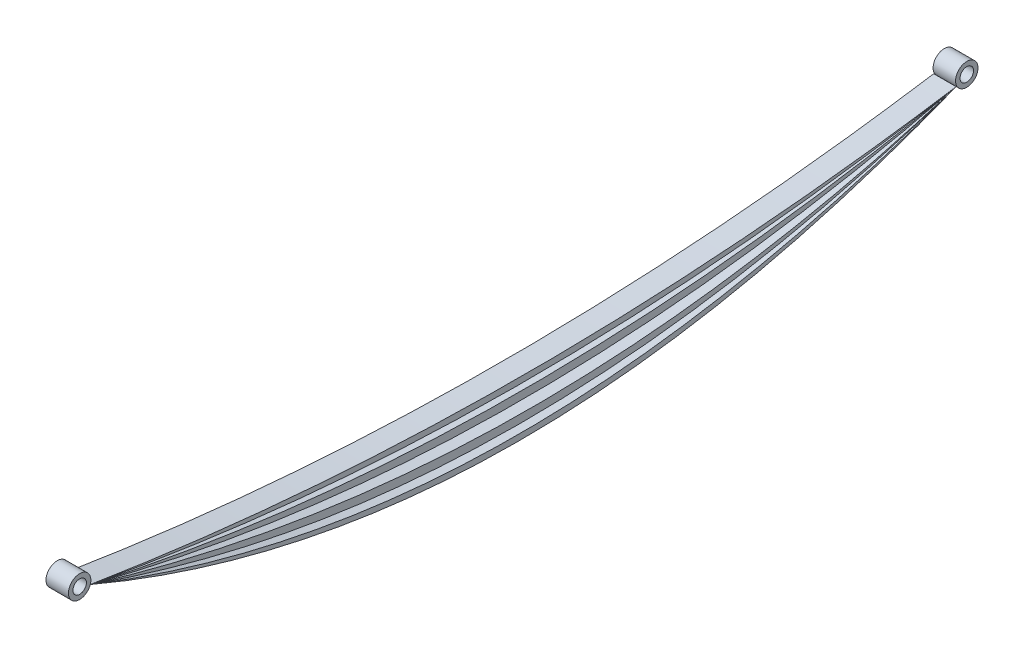
SolidWorks part; units mm, degrees
ref_plane "Front Plane" through (0, 0, 0) normal (0, 0, 1) x (1, 0, 0)
ref_plane "Top Plane" through (0, 0, 0) normal (0, 1, 0) x (1, 0, 0)
ref_plane "Right Plane" through (0, 0, 0) normal (1, 0, 0) x (0, 0, -1)
sketch "Sketch1" plane through (0, 0, 0) normal (1, 0, 0) x (0, 0, -1)
  line L1 (-127.7808, 42.4696) -> (65.0592, 42.08) construction
  line L2 (-31.3608, 56.4803) -> (-31.3608, 9.4168) construction
  circle A0 centre (-130.1522, 43.2614) radius 2.5
  circle A1 centre (67.4305, 43.2614) radius 2.5
  spline S0 degree 2 poles (-127.7808, 42.4696) (-31.7554, 26.9703) (65.0592, 42.08) knots 0 0 0 1 1 1
  spline S1 degree 2 poles (-127.7808, 42.4696) (-32.3332, 17.7907) (65.0592, 42.08) knots 0 0 0 1 1 1
  spline S2 degree 2 poles (-127.7808, 42.4696) (-33.8123, 2.5977) (65.0592, 42.08) knots 0 0 0 1 1 1
  spline S3 degree 2 poles (-127.7808, 42.4696) (-33.1527, 9.0475) (65.0592, 42.08) knots 0 0 0 1 1 1
  spline S4 degree 2 poles (-127.7808, 42.4696) (-32.196, 24.2429) (65.0592, 42.08) knots 0 0 0 1 1 1
  spline S5 degree 2 poles (-127.7808, 42.4696) (-32.7908, 21.3439) (65.0592, 42.08) knots 0 0 0 1 1 1
  spline S6 degree 2 poles (65.0592, 42.08) (-28.6723, 12.5923) (-127.7808, 42.4696) knots 0 0 0 1 1 1
  spline S7 degree 3 poles (65.0592, 42.08) (2.9557, 19.1426) (-60.749, 16.0514) (-127.7808, 42.4696) knots 0 0 0 0 1 1 1 1
  dimension "D2" = 5
  dimension "D1" = 192.84
  dimension "D3" = 197.5826
extrude "Boss-Extrude3" add sketch "Sketch1" along normal blind 5 contours A0 | A1 | S0 S4 | S5 S1 | S3 S6 | S2 S7
sketch "Sketch2" plane through (5, 0, 0) normal (1, 0, 0) x (0, 0, -1)
  circle A0 centre (67.4305, 43.2614) radius 1.5
  circle A1 centre (67.4305, 43.2614) radius 2.5
  circle A2 centre (67.4305, 43.2614) radius 2.5
  dimension "D1" = 0
  dimension "D2" = 1
sketch "Sketch3" plane through (5, 0, 0) normal (1, 0, 0) x (0, 0, -1)
  circle A0 centre (67.4305, 43.2614) radius 1.5
extrude "Cut-Extrude2" cut sketch "Sketch3" against normal blind 5
sketch "Sketch4" plane through (0, 0, 0) normal (-1, 0, 0) x (0, 0, 1)
  circle A0 centre (130.1522, 43.2614) radius 1.5
  circle A1 centre (130.1522, 43.2614) radius 2.5
  circle A2 centre (130.1522, 43.2614) radius 2.5
  circle A3 centre (130.1522, 43.2614) radius 1.5
  dimension "D1" = 0
  dimension "D2" = 1
extrude "Cut-Extrude3" cut sketch "Sketch4" against normal blind 5 contours A0
